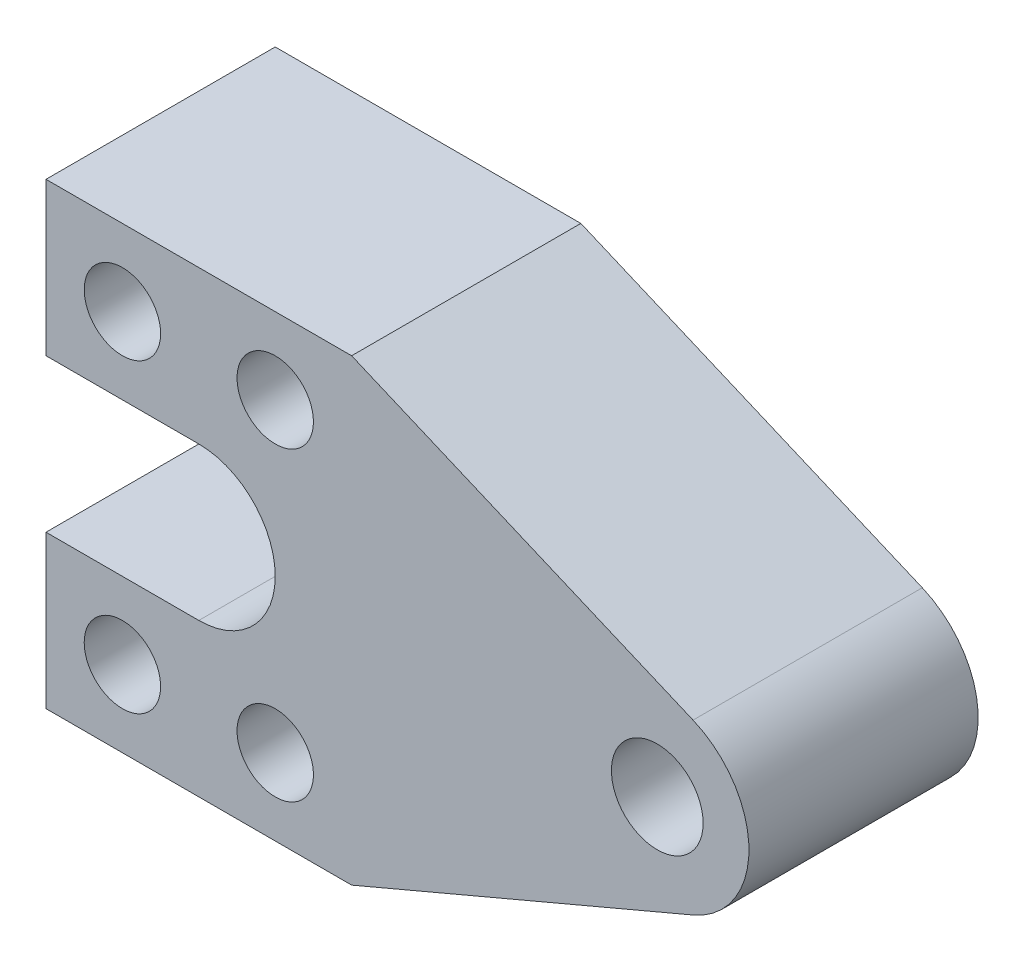
SolidWorks part; units mm, degrees
ref_plane "Front Plane" through (0, 0, 0) normal (0, 0, 1) x (1, 0, 0)
ref_plane "Top Plane" through (0, 0, 0) normal (0, 1, 0) x (1, 0, 0)
ref_plane "Right Plane" through (0, 0, 0) normal (1, 0, 0) x (0, 0, -1)
sketch "Sketch1" plane through (0, 0, 0) normal (0, 0, 1) x (1, 0, 0)
  line L1 (10, 10) -> (50, 10)
  line L2 (50, 10) -> (94.6856, 28.9526)
  line L3 (64.7656, 40) -> (-19118.5759, 40) construction
  line L4 (50, 70) -> (94.6856, 51.0474)
  line L5 (10, 70) -> (50, 70)
  line L6 (10, 50) -> (30, 50)
  line L7 (30, 30) -> (10, 30)
  line L8 (10, 30) -> (10, 10)
  line L12 (10, 70) -> (10, 50)
  arc A0 (94.6856, 28.9526) -> (94.6856, 51.0474) centre (90, 40) ccw
  arc A1 (30, 50) -> (30, 30) centre (30, 40) cw
  circle A2 centre (20, 60) radius 5
  circle A3 centre (40, 60) radius 5
  circle A4 centre (90, 40) radius 6
  circle A5 centre (40, 20) radius 5
  circle A6 centre (20, 20) radius 5
  point P16 (0, 0)
  dimension "D1" = 10
  dimension "D3" = 10
  dimension "D5" = 12
  dimension "D6" = 12
  dimension "D10" = 10
  dimension "D12" = 10
  dimension "D14" = 20
  dimension "D2" = 10
  dimension "D4" = 60
  dimension "D7" = 10
  dimension "D8" = 40
  dimension "D9" = 20
  dimension "D11" = 40
  dimension "D13" = 80
extrude "Boss-Extrude2" add sketch "Sketch1" along normal mid plane 30
